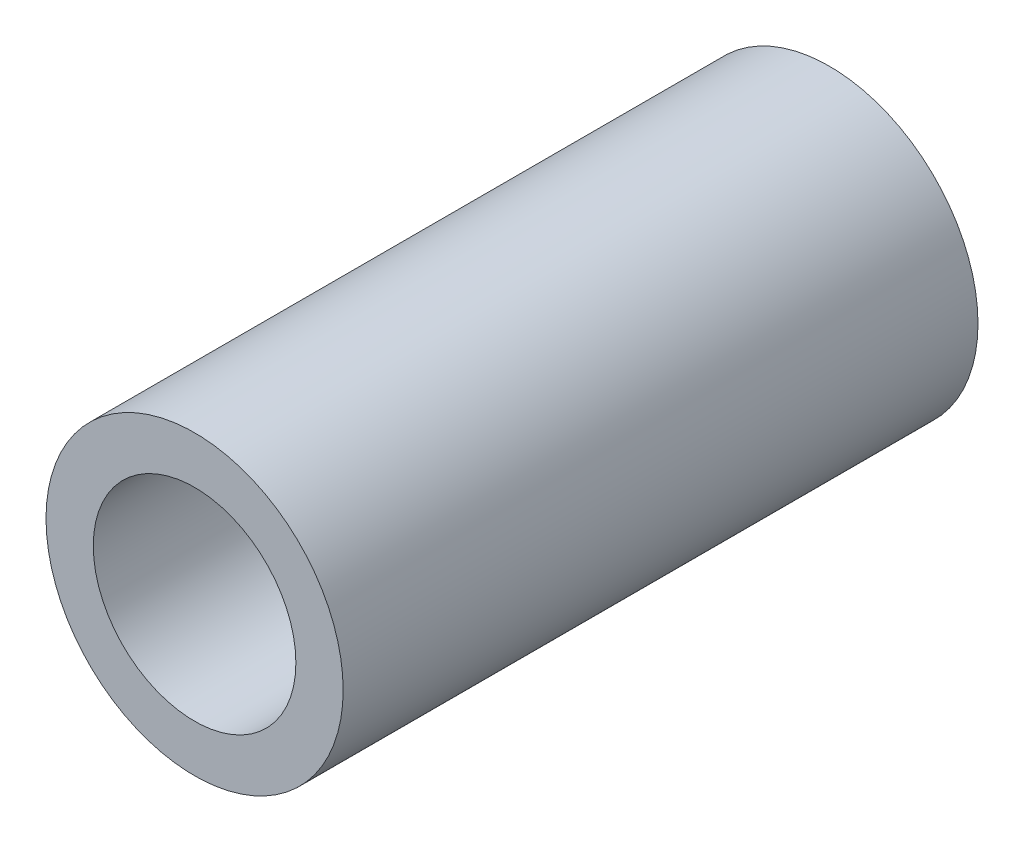
SolidWorks part; units mm, degrees
material "1060 Alloy"
ref_plane "Frontal Plane" through (0, 0, 0) normal (0, 0, 1) x (1, 0, 0)
ref_plane "Horizontal Plane" through (0, 0, 0) normal (0, 1, 0) x (1, 0, 0)
ref_plane "Profile Plane" through (0, 0, 0) normal (1, 0, 0) x (0, 0, -1)
sketch "Sketch1" plane through (0, 0, 0) normal (1, 0, 0) x (0, 0, -1)
  line L0 (-33.8255, 0) -> (36.745, 0) construction
  line L1 (0, -7.5) -> (-47, -7.5)
  line L2 (-47, -7.5) -> (-47, -11)
  line L3 (-47, -11) -> (0, -11)
  line L4 (0, -11) -> (0, -7.5)
  dimension "D1" = 7.5
  dimension "D2" = 11
  dimension "D3" = 47
revolve "Revolve1" add sketch "Sketch1" angle 360 about L0
